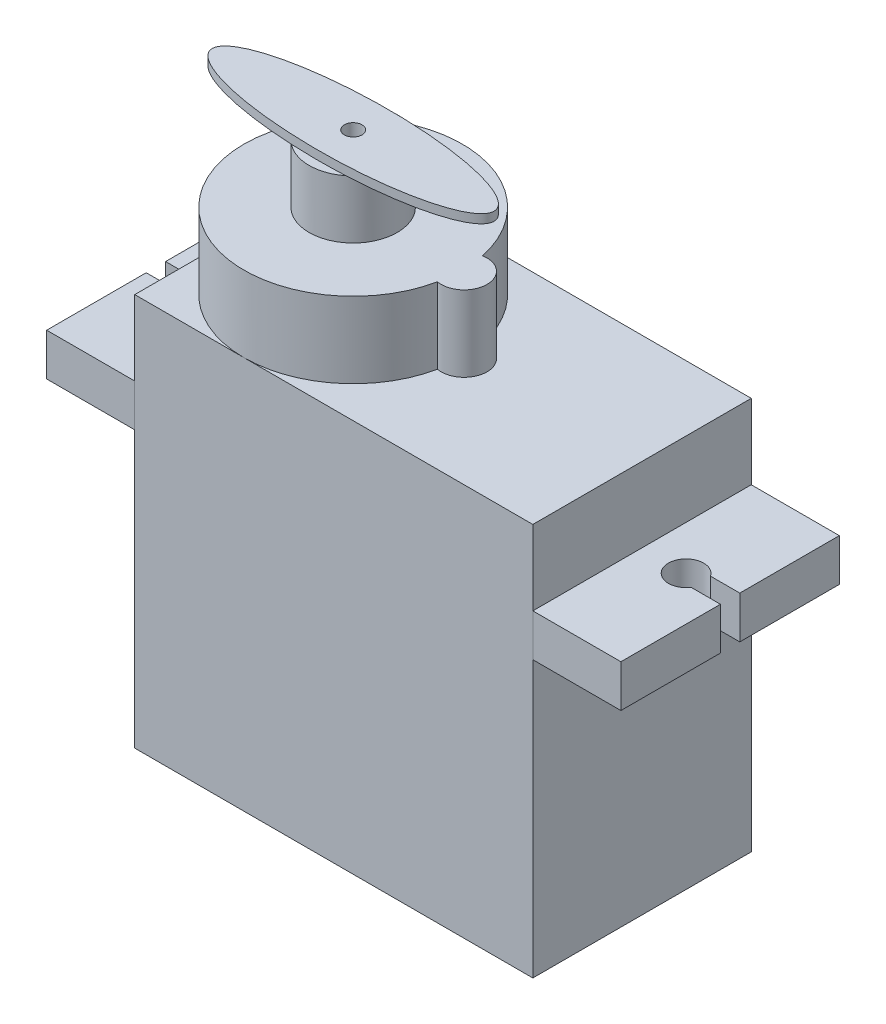
SolidWorks part; units mm, degrees
ref_plane "Front Plane" through (0, 0, 0) normal (0, 0, 1) x (1, 0, 0)
ref_plane "Top Plane" through (0, 0, 0) normal (0, 1, 0) x (1, 0, 0)
ref_plane "Right Plane" through (0, 0, 0) normal (1, 0, 0) x (0, 0, -1)
sketch "Sketch1" plane through (0, 0, 0) normal (0, 1, 0) x (1, 0, 0)
  line L1 (-11.3, -6.2) -> (11.3, -6.2)
  line L2 (-11.3, -6.2) -> (-11.3, 6.2)
  line L3 (-11.3, 6.2) -> (11.3, 6.2)
  line L4 (11.3, -6.2) -> (11.3, 6.2)
  line L5 (-11.3, -6.2) -> (11.3, 6.2) construction
  line L6 (-11.3, 6.2) -> (11.3, -6.2) construction
  point P0 (0, 0)
  dimension "D1" = 22.6
  dimension "D2" = 12.4
extrude "Boss-Extrude1" add sketch "Sketch1" along normal blind 22.3
sketch "Sketch2" plane through (11.3, 0, 0) normal (1, 0, 0) x (0, 0, -1)
  line L0 (-6.2, 22.3) -> (-6.2, 0) construction
  line L1 (-6.2, 18.05) -> (6.2, 18.05)
  line L2 (-6.2, 18.05) -> (-6.2, 15.65)
  line L3 (-6.2, 15.65) -> (6.2, 15.65)
  line L4 (6.2, 18.05) -> (6.2, 15.65)
  line L5 (6.2, 22.3) -> (6.2, 0) construction
  line L6 (-6.2, 22.3) -> (6.2, 22.3) construction
  dimension "D1" = 4.25
  dimension "D2" = 2.4
extrude "Boss-Extrude2" add sketch "Sketch2" along normal blind 5 separate body
sketch "Sketch3" plane through (-11.3, 0, 0) normal (-1, 0, 0) x (0, 0, 1)
  line L4 (6.2, 15.65) -> (6.2, 18.05)
  line L5 (-6.2, 15.65) -> (6.2, 15.65)
  line L6 (-6.2, 18.05) -> (-6.2, 15.65)
  line L7 (6.2, 18.05) -> (-6.2, 18.05)
  line L8 (6.2, 15.65) -> (6.2, 18.05)
  line L9 (-6.2, 15.65) -> (6.2, 15.65)
  line L10 (-6.2, 18.05) -> (-6.2, 15.65)
  line L11 (6.2, 18.05) -> (-6.2, 18.05)
  dimension "D1" = 0
extrude "Boss-Extrude3" add sketch "Sketch3" along normal blind 5 separate body
sketch "Sketch4" plane through (0, 18.05, 0) normal (0, 1, 0) x (1, 0, 0)
  line L0 (-16.3, -6.2) -> (-16.3, 6.2) construction
  line L1 (16.3, 6.2) -> (16.3, -6.2) construction
  line L3 (-16.3, 0.55) -> (-14.6352, 0.55)
  line L4 (-16.3, 0.55) -> (-16.3, -0.55)
  line L5 (-16.3, -0.55) -> (-14.6352, -0.55)
  line L7 (16.3, -0.55) -> (14.6352, -0.55)
  line L8 (16.3, -0.55) -> (16.3, 0.55)
  line L9 (16.3, 0.55) -> (14.6352, 0.55)
  arc A0 (-14.6352, -0.55) -> (-14.6352, 0.55) centre (-13.8, 0) ccw
  arc A1 (14.6352, 0.55) -> (14.6352, -0.55) centre (13.8, 0) ccw
  dimension "D1" = 2
  dimension "D2" = 2
  dimension "D4" = 2.5
  dimension "D3" = 2.5
  dimension "D5" = 1.1
  dimension "D6" = 0.55
  dimension "D7" = 1.1
  dimension "D8" = 0.55
extrude "Cut-Extrude1" cut sketch "Sketch4" against normal up to next (2.4 mm away)
sketch "Sketch5" plane through (0, 18.05, 0) normal (0, 1, 0) x (1, 0, 0)
  line L0 (16.3, 6.2) -> (16.3, -6.2) construction
  line L1 (14.6352, 0.55) -> (16.3, 0.55)
  line L3 (14.6352, -0.55) -> (16.3, -0.55)
  line L4 (16.3, 0.55) -> (16.3, -0.55)
  arc A0 (14.6352, 0.55) -> (14.6352, -0.55) centre (13.8, 0) ccw
  dimension "D1" = 2
  dimension "D2" = 1.1
  dimension "D3" = 0.55
  dimension "D4" = 2.5
extrude "Cut-Extrude2" cut sketch "Sketch5" against normal up to next (2.4 mm away) contours L1 L4 L3 A0
sketch "Sketch6" plane through (0, 22.3, 0) normal (0, 1, 0) x (1, 0, 0)
  line L0 (-11.3, 6.2) -> (-11.3, -6.2) construction
  line L1 (1.2, 1.3) -> (0.9622, 1.3)
  line L2 (1.2, -1.3) -> (0.9622, -1.3)
  arc A0 (0.9667, 1.2789) -> (0.9667, -1.2789) centre (-5.1, 0) ccw
  arc A1 (0.9667, -1.2789) -> (0.9667, 1.2789) centre (1.2, 0) ccw
  dimension "D2" = 12.4
  dimension "D3" = 2.6
  dimension "D1" = 6.2
  dimension "D4" = 6.3
extrude "Boss-Extrude4" add sketch "Sketch6" along normal blind 4.3 contours A1 A0
sketch "Sketch7" plane through (0, 26.6, 0) normal (0, 1, 0) x (1, 0, 0)
  circle A0 centre (-5.1, 0) radius 2.5
  dimension "D1" = 5
extrude "Boss-Extrude5" add sketch "Sketch7" along normal blind 3.3
sketch "Sketch8" plane through (-11.3, 0, 0) normal (-1, 0, 0) x (0, 0, 1)
  line L0 (-6.2, 0) -> (6.2, 0) construction
  circle A0 centre (-1.2, 4.5) radius 0.6
  circle A1 centre (0, 4.5) radius 0.6
  circle A2 centre (1.2, 4.5) radius 0.6
  dimension "D1" = 4.5
  dimension "D2" = 1.2
  dimension "D3" = 1.2
  dimension "D4" = 1.2
extrude "Boss-Extrude7" add sketch "Sketch8" along normal blind 2.3 separate body contours A1 | A0 | A2
sketch "Sketch9" plane through (0, 29.9, 0) normal (0, 1, 0) x (1, 0, 0)
  ellipse E0 centre (-5.1, 0) end of major axis (2.8988, 0) minor radius 2
extrude "Boss-Extrude10" add sketch "Sketch9" along normal blind 0.5
sketch "Sketch12" plane through (0, 30.4, 0) normal (0, 1, 0) x (1, 0, 0)
  circle A0 centre (-5.1, 0) radius 0.5
extrude "Cut-Extrude4" cut sketch "Sketch12" against normal blind 1
